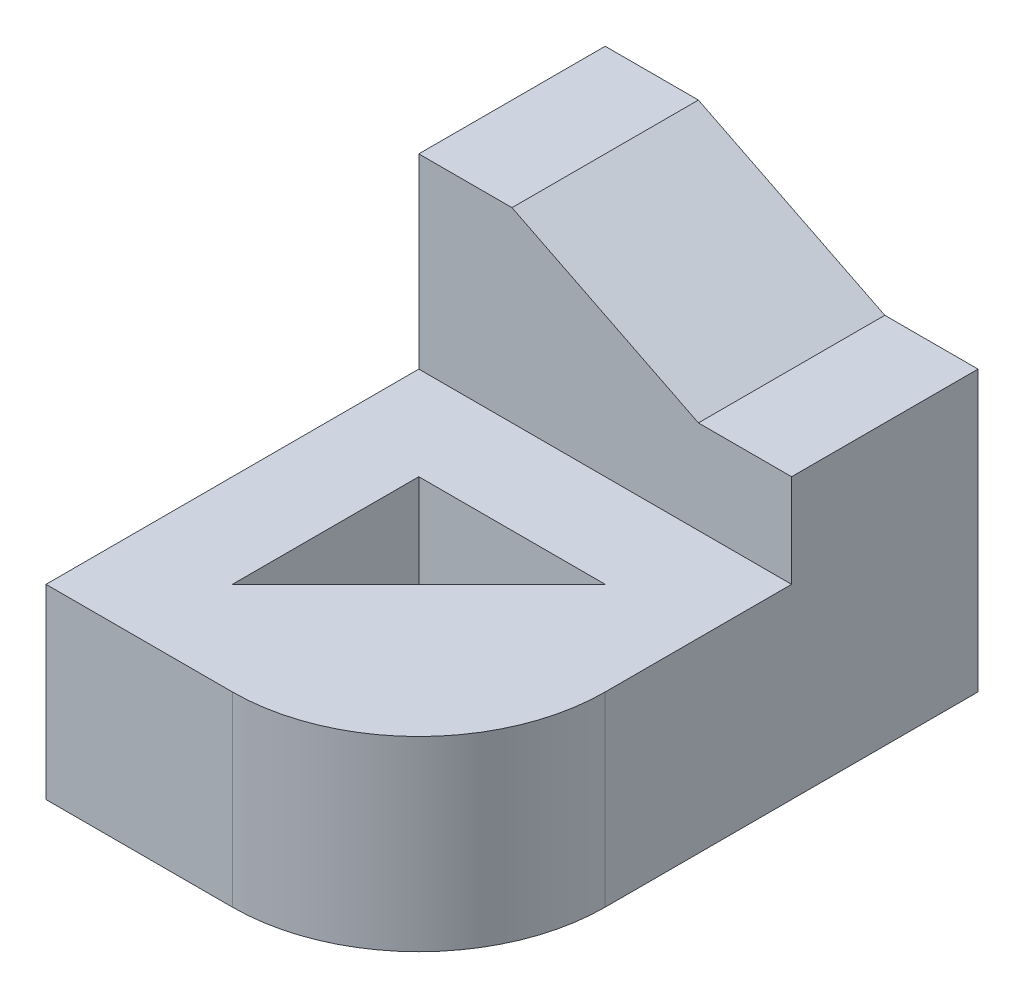
SolidWorks part; units mm, degrees
ref_plane "Front Plane" through (0, 0, 0) normal (0, 0, 1) x (1, 0, 0)
ref_plane "Top Plane" through (0, 0, 0) normal (0, 1, 0) x (1, 0, 0)
ref_plane "Right Plane" through (0, 0, 0) normal (1, 0, 0) x (0, 0, -1)
sketch "Sketch1" plane through (0, 0, 0) normal (0, 1, 0) x (1, 0, 0)
  line L0 (-10, 0) -> (-10, -20)
  line L1 (-20, 30) -> (20, 30)
  line L2 (-20, 30) -> (-20, -30)
  line L3 (-20, -30) -> (0, -30)
  line L4 (20, 30) -> (20, -10)
  line L5 (-20, 30) -> (20, -30) construction
  line L6 (-20, -30) -> (20, 30) construction
  line L7 (-10, -20) -> (10, 0)
  line L8 (10, 0) -> (-10, 0)
  arc A0 (0, -30) -> (20, -10) centre (0, -10) ccw
  point P0 (0, 0)
  dimension "D3" = 20
  dimension "D1" = 60
  dimension "D2" = 40
  dimension "D4" = 20
  dimension "D5" = 30
  dimension "D6" = 10
  dimension "D7" = 20
extrude "Boss-Extrude1" add sketch "Sketch1" along normal blind 20
sketch "Sketch2" plane through (0, 0, -30) normal (0, 0, -1) x (-1, 0, 0)
  line L0 (20, 20) -> (20, 40)
  line L1 (20, 40) -> (10, 40)
  line L2 (10, 40) -> (-10, 30)
  line L3 (-10, 30) -> (-20, 30)
  line L4 (-20, 30) -> (-20, 20)
  line L5 (-20, 20) -> (20, 20)
  dimension "D1" = 10
  dimension "D2" = 10
  dimension "D3" = 10
  dimension "D4" = 20
extrude "Boss-Extrude2" add sketch "Sketch2" against normal blind 20
